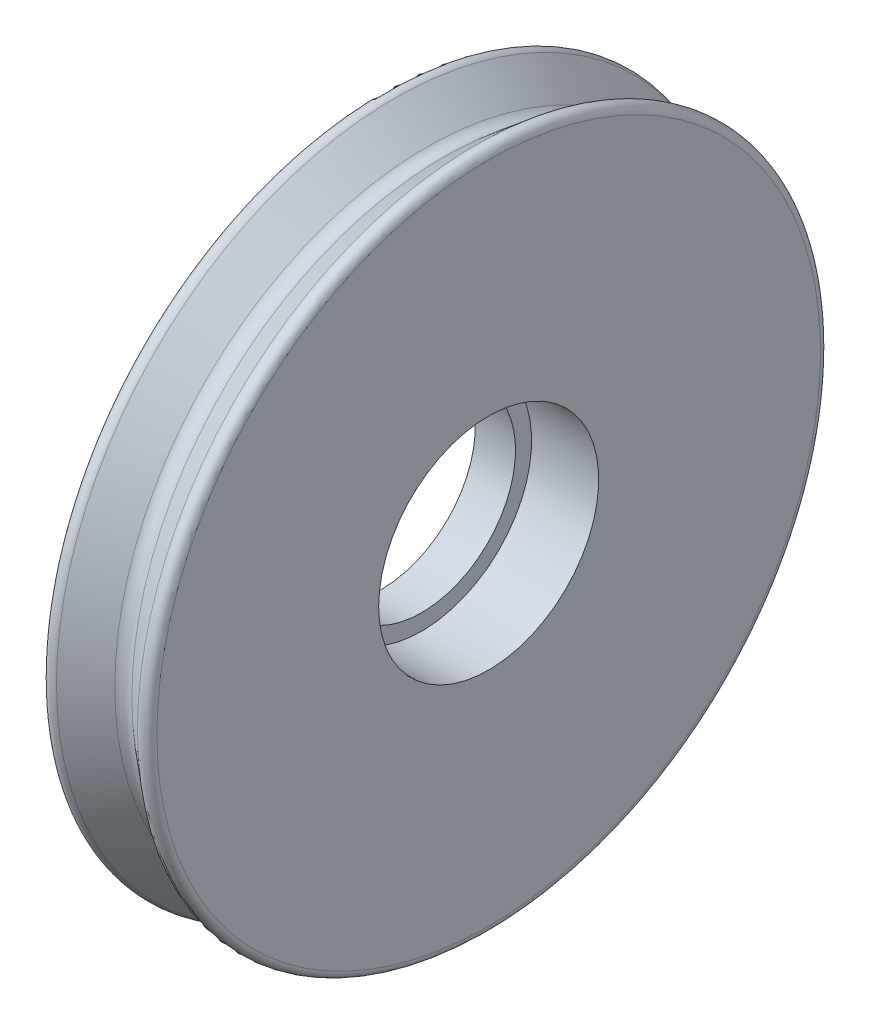
SolidWorks part; units mm, degrees
material "ABS"
ref_plane "Front Plane" through (0, 0, 0) normal (0, 0, 1) x (1, 0, 0)
ref_plane "Top Plane" through (0, 0, 0) normal (0, 1, 0) x (1, 0, 0)
ref_plane "Right Plane" through (0, 0, 0) normal (1, 0, 0) x (0, 0, -1)
sketch "Sketch1" plane through (0, 0, 0) normal (0, 0, 1) x (1, 0, 0)
  line L0 (0, 3.5) -> (0, 13)
  line L2 (0, 13) -> (1.6821, 11.6141)
  line L3 (2.3179, 11.6141) -> (4, 13)
  line L5 (4, 13) -> (4, 4.1)
  line L6 (4, 4.1) -> (1.5, 4.1)
  line L7 (1.5, 4.1) -> (1.5, 3.5)
  line L8 (1.5, 3.5) -> (0, 3.5)
  line L9 (0, 0) -> (4, 0) construction
  arc A0 (1.6821, 11.6141) -> (2.3179, 11.6141) centre (2, 12) ccw
  dimension "D8" = 0.5
  dimension "D1" = 12
  dimension "D2" = 4
  dimension "D3" = 2.5
  dimension "D4" = 4.1
  dimension "D5" = 3.5
  dimension "D6" = 13
  dimension "D9" = 2
revolve "Revolve1" add sketch "Sketch1" angle 360 about L9
ref_plane "pulley_plane" through (2, 0, 0) normal (-1, 0, 0) x (0, 0, 1)
fillet "Fillet1" radius 0.3 2 edges at (4, 0, 13) (0, 0, 13)
